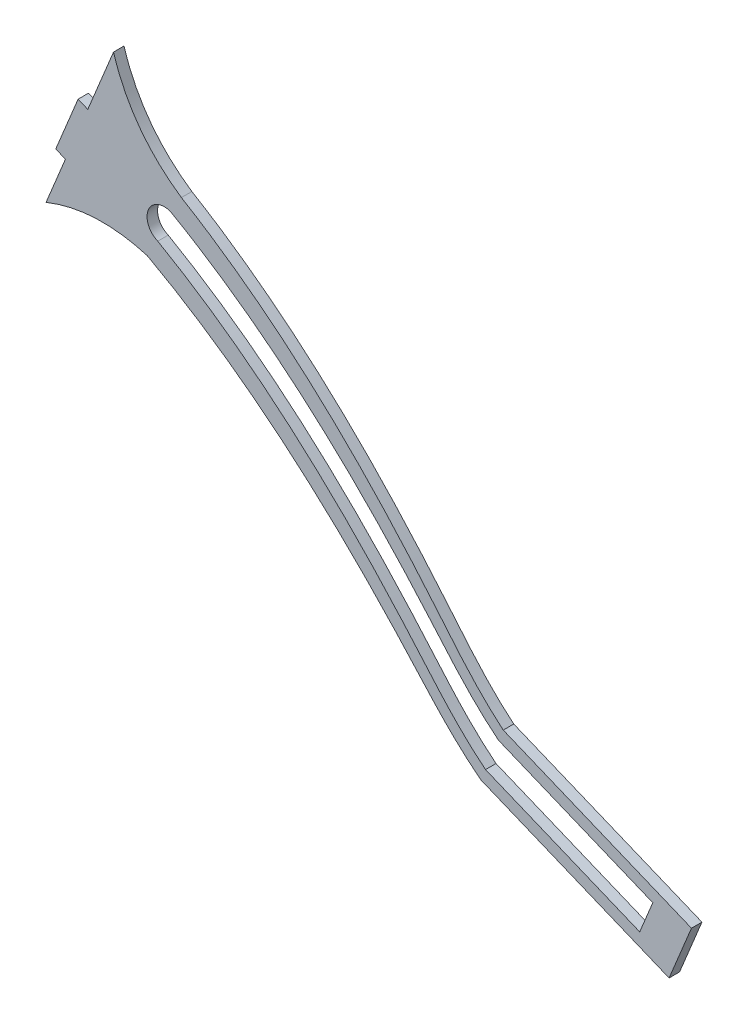
SolidWorks part; units mm, degrees
ref_plane "Front Plane" through (0, 0, 0) normal (0, 0, 1) x (1, 0, 0)
ref_plane "Top Plane" through (0, 0, 0) normal (0, 1, 0) x (1, 0, 0)
ref_plane "Right Plane" through (0, 0, 0) normal (1, 0, 0) x (0, 0, -1)
sketch "Sketch2" plane through (0, 0, 324.6091) normal (0, 0, 1) x (1, 0, 0)
  line L0 (-16.9001, -8.1832) -> (72.8165, -45.1124)
  line L1 (72.8165, -45.1124) -> (83.4743, -19.2201)
  line L2 (83.4743, -19.2201) -> (-6.2423, 17.7091)
  line L3 (1.577, -0.6491) -> (-11.5712, 4.763) construction
  line L4 (-31.9742, 22.0287) -> (-36.491, 11.0554) construction
  line L5 (375.3074, 944.6533) -> (-8.45, 12.3457) construction
  line L6 (65.0498, -17.9083) -> (-8.45, 12.3457)
  line L7 (-11.5712, 4.763) -> (78.2012, -32.1893) construction
  line L8 (-14.6924, -2.8198) -> (58.8073, -33.0738)
  line L9 (58.8073, -33.0738) -> (65.0498, -17.9083)
  line L10 (-14.6924, -2.8198) -> (-393.3529, -922.7448) construction
  line L11 (-31.5661, 12.9932) -> (-986.2799, 405.9735) construction
  line L12 (-224.1829, 126.5929) -> (-214.9454, 149.0346)
  line L15 (-208.9112, 176.8301) -> (-204.2876, 174.9269)
  line L16 (-219.569, 150.9378) -> (-214.9454, 149.0346)
  line L17 (-219.569, 150.9378) -> (-208.9112, 176.8301)
  line L18 (-204.2876, 174.9269) -> (-192.0222, 204.7247)
  arc A0 (-159.6673, 160.8235) -> (-175.9119, 128.6971) centre (-167.8281, 144.7798) ccw construction
  arc A1 (-164.7069, 152.3625) -> (-170.9494, 137.197) centre (-167.8281, 144.7798) ccw
  spline S0 degree 3 poles (-14.6924, -2.8198) (-27.809, 7.6384) (-72.367, 61.955) (-124.0787, 110.4292) (-170.9494, 137.197) knots 0 0 0 0 0.237148 1 1 1 1
  spline S1 degree 3 poles (-11.5712, 4.763) (-24.6878, 15.2212) (-69.2458, 69.5377) (-120.9575, 118.0119) (-167.8281, 144.7798) knots 0 0 0 0 0.237148 1 1 1 1 construction
  spline S2 degree 3 poles (-8.45, 12.3457) (-21.5666, 22.8039) (-66.1246, 77.1205) (-117.8363, 125.5947) (-164.7069, 152.3625) knots 0 0 0 0 0.237148 1 1 1 1
  spline S3 degree 3 poles (-6.2423, 17.7091) (-19.1471, 28.4276) (-62.6097, 83.6245) (-113.3415, 133.1235) (-159.6673, 160.8235) knots 0 0 0 0 0.237148 1 1 1 1
  spline S4 degree 3 poles (-16.9001, -8.1832) (-30.2222, 2.012) (-75.852, 55.4313) (-128.518, 102.8671) (-175.9119, 128.6971) knots 0 0 0 0 0.237148 1 1 1 1
  spline S5 degree 2 poles (-175.9119, 128.6971) (-200.798, 136.066) (-224.1829, 126.5929) knots 0 0 0 1 1 1
  spline S6 degree 2 poles (-192.0222, 204.7247) (-183.5257, 177.0768) (-159.6673, 160.8235) knots 0 0 0 1 1 1
  dimension "D1" = 14
  dimension "D9" = 18
  dimension "D8" = 8.2
  dimension "D2" = 14
  dimension "D3" = 8.2
  dimension "D5" = 8.2
  dimension "D6" = 97.0198
  dimension "D7" = 79.4828
extrude "Boss-Extrude1" add sketch "Sketch2" against normal blind 5
ref_plane "Plane1" through (0, 0, 322.1091) normal (0, 0, 1) x (1, 0, 0)
sketch "Sketch3" plane through (0, 0, 322.1091) normal (0, 0, 1) x (1, 0, 0)
  line L0 (184946.5517, -76127.887) -> (-11.5712, 4.763) construction
  line L1 (78.2012, -32.1893) -> (-10.2271, 4.2097)
  arc A0 (-10.2271, 4.2097) -> (-12.7508, 5.7155) centre (-6.4207, 13.4569) cw
  spline S0 degree 3 poles (1657.7295, 1090.3652) (103.7075, -181.553) (-104.9422, 227.4638) (-605.4971, 398.0877) (-1764.9346, -986.6174) knots -1.662687 -1.662687 -1.662687 -1.662687 0.237148 4.725156 4.725156 4.725156 4.725156 only from (-11.5712, 4.763) to (-167.8281, 144.7798) construction
  spline S1 degree 3 poles (-12.7508, 5.7155) (-25.3254, 15.9976) (-69.6156, 69.8843) (-120.9575, 118.0119) (-167.8281, 144.7798) knots 0.007151 0.007151 0.007151 0.007151 0.237148 1 1 1 1
  dimension "D1" = 10
